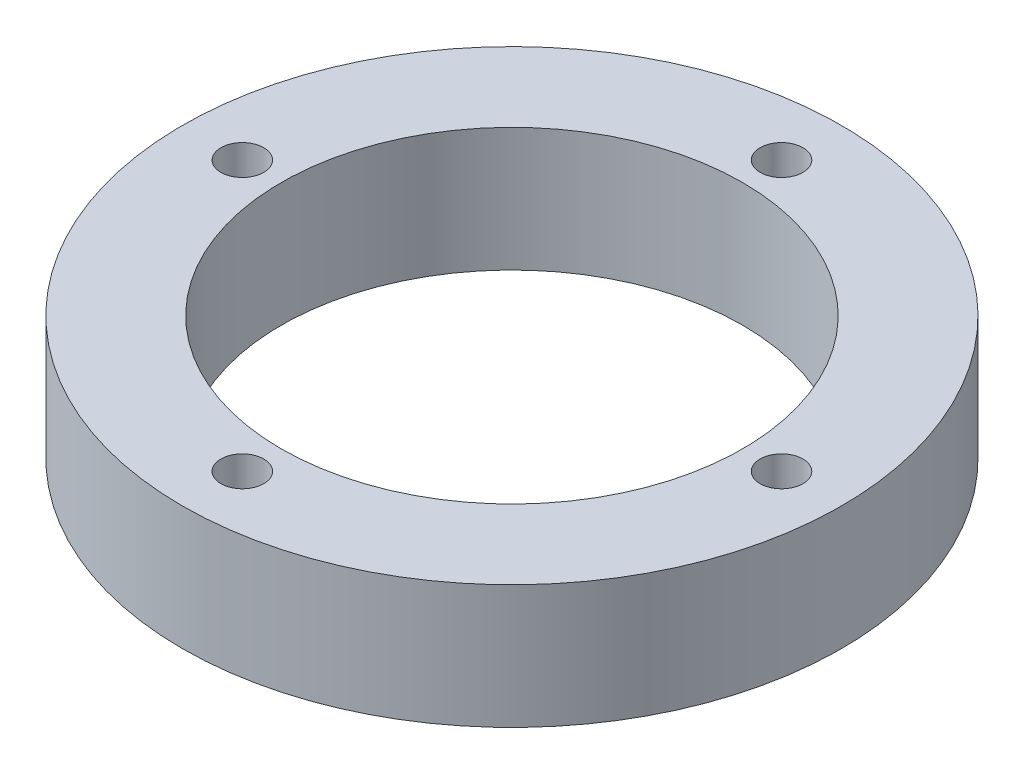
SolidWorks part; units mm, degrees
ref_plane "Front Plane" through (0, 0, 0) normal (0, 0, 1) x (1, 0, 0)
ref_plane "Top Plane" through (0, 0, 0) normal (0, 1, 0) x (1, 0, 0)
ref_plane "Right Plane" through (0, 0, 0) normal (1, 0, 0) x (0, 0, -1)
sketch "Sketch1" plane through (0, 0, 0) normal (0, 1, 0) x (1, 0, 0)
  line L0 (-37.9882, 0) -> (33.7078, 0) construction
  line L1 (0, -33.2919) -> (0, 34.04) construction
  circle A0 centre (0, 0) radius 25.4
  circle A1 centre (0, 0) radius 17.78
  circle A2 centre (0, 20.7772) radius 1.651
  circle A3 centre (0, -20.7772) radius 1.651
  circle A4 centre (20.7772, 0) radius 1.651
  circle A5 centre (-20.7772, 0) radius 1.651
  dimension "D1" = 50.8
  dimension "D2" = 35.56
  dimension "D3" = 20.7772
extrude "Extrude1" add sketch "Sketch1" along normal blind 9.525
